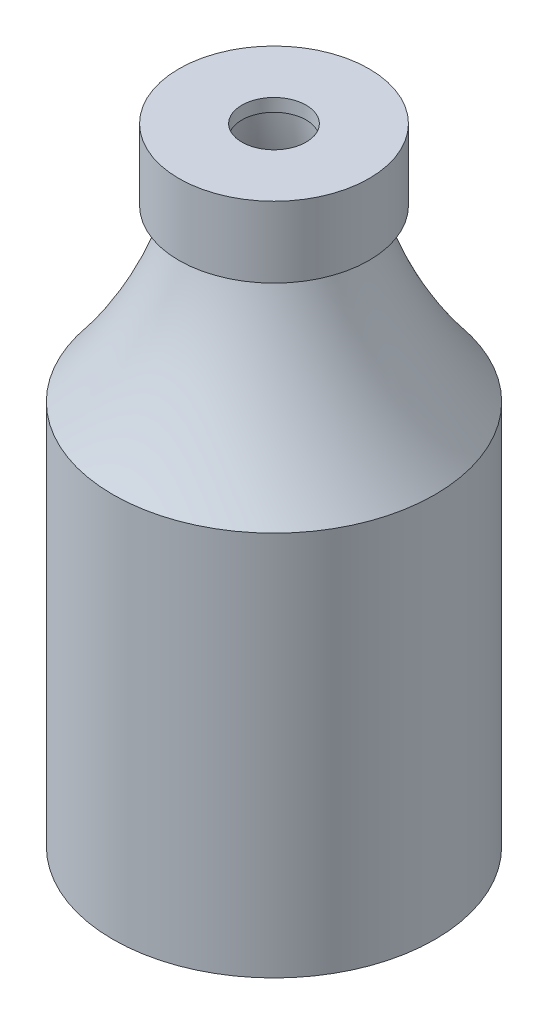
SolidWorks part; units mm, degrees
ref_plane "Front Plane" through (0, 0, 0) normal (0, 0, 1) x (1, 0, 0)
ref_plane "Top Plane" through (0, 0, 0) normal (0, 1, 0) x (1, 0, 0)
ref_plane "Right Plane" through (0, 0, 0) normal (1, 0, 0) x (0, 0, -1)
sketch "Sketch2" plane through (0, 0, 0) normal (0, 0, 1) x (1, 0, 0)
  line L0 (-11.9477, 77.0566) -> (-11.9477, -170.6286)
  line L1 (-11.9477, -170.6286) -> (-75.6381, -170.6286)
  line L2 (-11.9477, 77.0566) -> (-37.3477, 77.0566)
  line L3 (-75.6381, -170.6286) -> (-75.6381, -18.2286)
  spline S0 degree 2 poles (-75.6381, -18.2286) (-41.4078, 25.6039) (-37.3477, 77.0566) knots 0 0 0 1 1 1
  point P6 (-37.0874, 68.0079)
  point P7 (-37.9064, 71.2346)
  dimension "D1" = 25.4
revolve "Revolve1" add sketch "Sketch2" angle 360 about L0
sketch "Sketch3" plane through (0, 0, 0) normal (0, 0, 1) x (1, 0, 0)
  line L0 (-41.9469, 48.9976) -> (-49.5669, 48.9976)
  line L1 (-49.5669, 77.0566) -> (-37.3477, 77.0566)
  line L2 (-49.5669, 48.9976) -> (-49.5669, 77.0566)
  line L4 (-11.9477, -170.6286) -> (-11.9477, 77.0566)
  line L5 (-75.6381, -170.6286) -> (-11.9477, -170.6286)
  line L6 (-75.6381, -18.2286) -> (-75.6381, -170.6286)
  line L7 (-11.9477, 77.0566) -> (-37.3477, 77.0566)
  line L8 (-11.9477, -170.6286) -> (-11.9477, 77.0566)
  line L9 (-75.6381, -170.6286) -> (-11.9477, -170.6286)
  line L10 (-75.6381, -18.2286) -> (-75.6381, -170.6286)
  line L11 (-11.9477, 77.0566) -> (-37.3477, 77.0566)
  parabola Q1 (-37.3477, 77.0566) -> (-75.6381, -18.2286) focus (-122.6079, 69.3704) apex (-41.9469, 48.9976)
  parabola Q2 (-37.3477, 77.0566) -> (-75.6381, -18.2286) focus (-122.6079, 69.3704) apex (-41.9469, 48.9976)
  point P11 (-41.9469, 48.9976)
  dimension "D2" = 28.059
  dimension "D1" = 0
revolve "Revolve2" add sketch "Sketch3" angle 360 about L8
sketch "Sketch4" plane through (0, 77.0566, 0) normal (0, 1, 0) x (1, 0, 0)
  circle A0 centre (-11.9477, 0) radius 12.7
  circle A1 centre (-11.9477, 0) radius 37.6192 construction
  dimension "D1" = 25.4
  dimension "D2" = 11.9477
extrude "Cut-Extrude1" cut sketch "Sketch4" against normal blind 50.8
sketch "Sketch5" plane through (0, 0, 0) normal (0, 0, 1) x (1, 0, 0)
  line L8 (-17.0277, -165.5486) -> (-17.0277, 71.9766)
  line L9 (-70.5581, -165.5486) -> (-17.0277, -165.5486)
  line L10 (-70.5581, -19.9658) -> (-70.5581, -165.5486)
  line L11 (-17.0277, 71.9766) -> (-32.715, 71.9766)
  line L12 (-17.0277, -165.5486) -> (-17.0277, 71.9766)
  line L13 (-70.5581, -165.5486) -> (-17.0277, -165.5486)
  line L14 (-70.5581, -19.9658) -> (-70.5581, -165.5486)
  line L15 (-17.0277, 71.9766) -> (-32.715, 71.9766)
  spline S0 degree 3 poles (-4347.8514, 2490.4235) (-1038.7167, 1131.1328) (108.1338, 391.1483) (-45.8997, 21.5873) (-46.7425, 19.662) (-48.5, 15.8322) (-49.4163, 13.9247) (-52.2566, 8.264) (-54.2741, 4.5673) (-284.3471, -386.1614) (-1840.114, 52.1928) (3055.4435, -3519.9893) knots -11.370771 -11.370771 -11.370771 -11.370771 0.5 0.5 0.5625 0.5625 0.625 0.625 0.75 0.75 14.101237 14.101237 14.101237 14.101237 only from (-32.715, 71.9766) to (-70.5581, -19.9658)
  spline S1 degree 3 poles (-32.715, 71.9766) (-34.4915, 55.1524) (-38.639, 39.0073) (-45.8997, 21.5873) (-46.7425, 19.662) (-48.5, 15.8322) (-49.4163, 13.9247) (-52.2566, 8.264) (-54.2741, 4.5673) (-60.6763, -6.3054) (-65.41, -13.2644) (-70.5581, -19.9658) knots 0 0 0 0 0.5 0.5 0.5625 0.5625 0.625 0.625 0.75 0.75 1 1 1 1
  dimension "D1" = 5.08
revolve "Cut-Revolve1" cut sketch "Sketch5" angle 360 about L12
